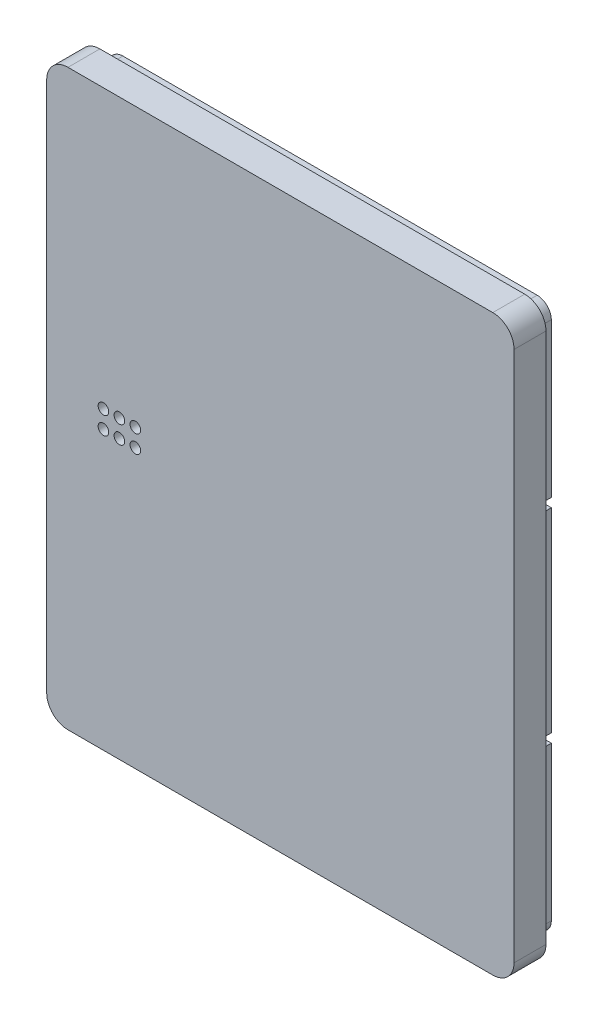
SolidWorks part; units mm, degrees
ref_plane "Alzado" through (0, 0, 0) normal (0, 0, 1) x (1, 0, 0)
ref_plane "Planta" through (0, 0, 0) normal (0, 1, 0) x (1, 0, 0)
ref_plane "Vista lateral" through (0, 0, 0) normal (1, 0, 0) x (0, 0, -1)
sketch "Croquis1" plane through (0, 0, 0) normal (0, 0, 1) x (1, 0, 0)
  line L1 (0, 0) -> (131.8, 0)
  line L2 (0, 0) -> (0, -161.8)
  line L3 (0, -161.8) -> (131.8, -161.8)
  line L4 (131.8, 0) -> (131.8, -161.8)
  dimension "D1" = 161.8
  dimension "D2" = 131.8
extrude "Saliente-Extruir1" add sketch "Croquis1" along normal blind 9
sketch "Croquis2" plane through (0, 0, 0) normal (0, 0, -1) x (-1, 0, 0)
  line L0 (-131.8, 0) -> (0, 0) construction
  line L1 (-128.3, -3.5) -> (-3.5, -3.5)
  line L2 (-128.3, -3.5) -> (-128.3, -158.3)
  line L3 (-128.3, -158.3) -> (-3.5, -158.3)
  line L4 (-3.5, -3.5) -> (-3.5, -158.3)
  line L5 (0, -161.8) -> (-131.8, -161.8) construction
  line L6 (-131.8, -161.8) -> (-131.8, 0) construction
  line L7 (0, 0) -> (0, -161.8) construction
  dimension "D1" = 3.5
  dimension "D2" = 3.5
  dimension "D3" = 3.5
  dimension "D4" = 3.5
extrude "Saliente-Extruir2" add sketch "Croquis2" along normal blind 5
sketch "Croquis4" plane through (0, 0, -5) normal (0, 0, -1) x (-1, 0, 0)
  line L0 (-3.5, -3.5) -> (-128.3, -3.5) construction
  line L1 (-126.3, -5.5) -> (-5.5, -5.5)
  line L2 (-126.3, -5.5) -> (-126.3, -156.3)
  line L3 (-126.3, -156.3) -> (-5.5, -156.3)
  line L4 (-5.5, -5.5) -> (-5.5, -156.3)
  line L5 (-128.3, -3.5) -> (-128.3, -158.3) construction
  line L6 (-128.3, -158.3) -> (-3.5, -158.3) construction
  line L7 (-3.5, -158.3) -> (-3.5, -3.5) construction
  line L18 (-3.5, -3.5) -> (-128.3, -3.5) construction
  line L19 (-128.3, -158.3) -> (-3.5, -158.3) construction
  line L20 (-128.3, -3.5) -> (-128.3, -158.3) construction
  line L21 (-3.5, -158.3) -> (-3.5, -3.5) construction
  dimension "D1" = 2
  dimension "D2" = 2
  dimension "D3" = 2
  dimension "D4" = 2
extrude "Cortar-Extruir1" cut sketch "Croquis4" against normal blind 10
fillet "Redondeo1" radius 4 1 edges at (128.3, -3.5, -2.5)
fillet "Redondeo2" radius 2 1 edges at (5.5, -5.5, 0)
fillet "Redondeo3" radius 4 1 edges at (3.5, -3.5, -2.5)
fillet "Redondeo4" radius 4 1 edges at (3.5, -158.3, -2.5)
fillet "Redondeo5" radius 2 1 edges at (5.5, -156.3, 0)
fillet "Redondeo6" radius 4 1 edges at (128.3, -158.3, -2.5)
fillet "Redondeo7" radius 2 2 edges at (126.3, -5.5, 0) (126.3, -156.3, 0)
fillet "Redondeo8" radius 6 4 edges at (131.8, 0, 4.5) (131.8, -161.8, 4.5) (0, -161.8, 4.5) (0, 0, 4.5)
sketch "Croquis9" plane through (0, 0, -5) normal (0, 0, -1) x (-1, 0, 0)
  line L0 (-128.3, -7.5) -> (-128.3, -154.3) construction
  line L1 (-128.3, -50.9) -> (-3.5, -50.9)
  line L2 (-128.3, -50.9) -> (-128.3, -53.4)
  line L3 (-128.3, -53.4) -> (-3.5, -53.4)
  line L4 (-3.5, -50.9) -> (-3.5, -53.4)
  line L5 (-3.5, -154.3) -> (-3.5, -7.5) construction
  line L6 (-125.8, 0) -> (-6, 0) construction
  line L7 (-6, -161.8) -> (-125.8, -161.8) construction
  line L8 (-128.3, -108.4) -> (-3.5, -108.4)
  line L9 (-128.3, -108.4) -> (-128.3, -110.9)
  line L10 (-128.3, -110.9) -> (-3.5, -110.9)
  line L11 (-3.5, -108.4) -> (-3.5, -110.9)
  dimension "D1" = 2.5
  dimension "D2" = 50.9
  dimension "D3" = 2.5
  dimension "D4" = 50.9
extrude "Cortar-Extruir3" cut sketch "Croquis9" against normal blind 5
sketch "Croquis11" plane through (0, 0, 5) normal (0, 0, -1) x (-1, 0, 0)
  line L1 (-28, -75.9) -> (-12, -75.9)
  line L2 (-28, -75.9) -> (-28, -85.9)
  line L3 (-28, -85.9) -> (-12, -85.9)
  line L4 (-12, -75.9) -> (-12, -85.9)
  line L6 (-5.5, -53.4) -> (-3.5, -53.4) construction
  line L8 (-3.5, -108.4) -> (-3.5, -53.4) construction
  circle A0 centre (-16, -78.4) radius 1.5
  circle A1 centre (-16, -83.4) radius 1.5
  circle A2 centre (-20.5, -78.4) radius 1.5
  circle A3 centre (-20.5, -83.4) radius 1.5
  circle A4 centre (-25, -78.4) radius 1.5
  circle A5 centre (-25, -83.4) radius 1.5
  dimension "D4" = 3
  dimension "D1" = 22.5
  dimension "D2" = 10
  dimension "D3" = 16
  dimension "D5" = 4.5
  dimension "D6" = 4.5
  dimension "D7" = 4
  dimension "D8" = 12.5
  dimension "D9" = 2.5
  dimension "D10" = 2.5
extrude "Cortar-Extruir6" cut sketch "Croquis11" against normal blind 9 contours A4 | A5 | A3 | A1 | A2 | A0
